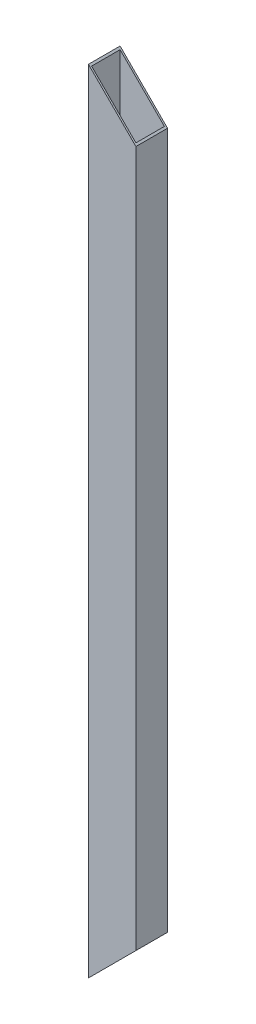
SolidWorks part; units mm, degrees
ref_plane "Ön Düzlem" through (0, 0, 0) normal (0, 0, 1) x (1, 0, 0)
ref_plane "Üst Düzlem" through (0, 0, 0) normal (0, 1, 0) x (1, 0, 0)
ref_plane "Sağ Düzlem" through (0, 0, 0) normal (1, 0, 0) x (0, 0, -1)
sketch "Çizim1" plane through (0, 0, 0) normal (0, 1, 0) x (1, 0, 0)
  line L1 (0, 0) -> (60, 0)
  line L2 (0, 0) -> (0, 40)
  line L3 (0, 40) -> (60, 40)
  line L4 (60, 0) -> (60, 40)
  line L9 (2, 38) -> (58, 38)
  line L10 (2, 38) -> (2, 2)
  line L11 (2, 2) -> (58, 2)
  line L12 (58, 38) -> (58, 2)
  dimension "D1" = 60
  dimension "D2" = 40
  dimension "D3" = 2
  dimension "D4" = 2
  dimension "D5" = 2
  dimension "D6" = 2
extrude "Yükseklik-Ekstrüzyon1" add sketch "Çizim1" along normal blind 1000
sketch "Çizim2" plane through (0, 0, -40) normal (0, 0, -1) x (-1, 0, 0)
  line L0 (0, 1000) -> (-60, 940)
  line L1 (-60, 1000) -> (-60, 0) construction
  line L2 (0, 0) -> (-60, 60)
  line L6 (-60, 0) -> (0, 0)
  line L7 (0, 0) -> (0, 1000)
  line L8 (0, 1000) -> (-60, 1000)
  line L9 (-60, 1000) -> (-60, 0)
  line L10 (-60, 0) -> (0, 0)
  line L11 (0, 0) -> (0, 1000)
  line L12 (0, 1000) -> (-60, 1000)
  line L13 (-60, 1000) -> (-60, 0)
  line M7 (-60, 0) -> (0, 0)
  line M9 (0, 1000) -> (-60, 1000)
  line M10 (-60, 1000) -> (-60, 0)
  dimension "D2" = 45
  dimension "D3" = 45
  dimension "D1" = 0
extrude "Kes-Ekstrüzyon1" cut sketch "Çizim2" against normal blind 700 contours L0 M9 M10 | L2 M7 M10
